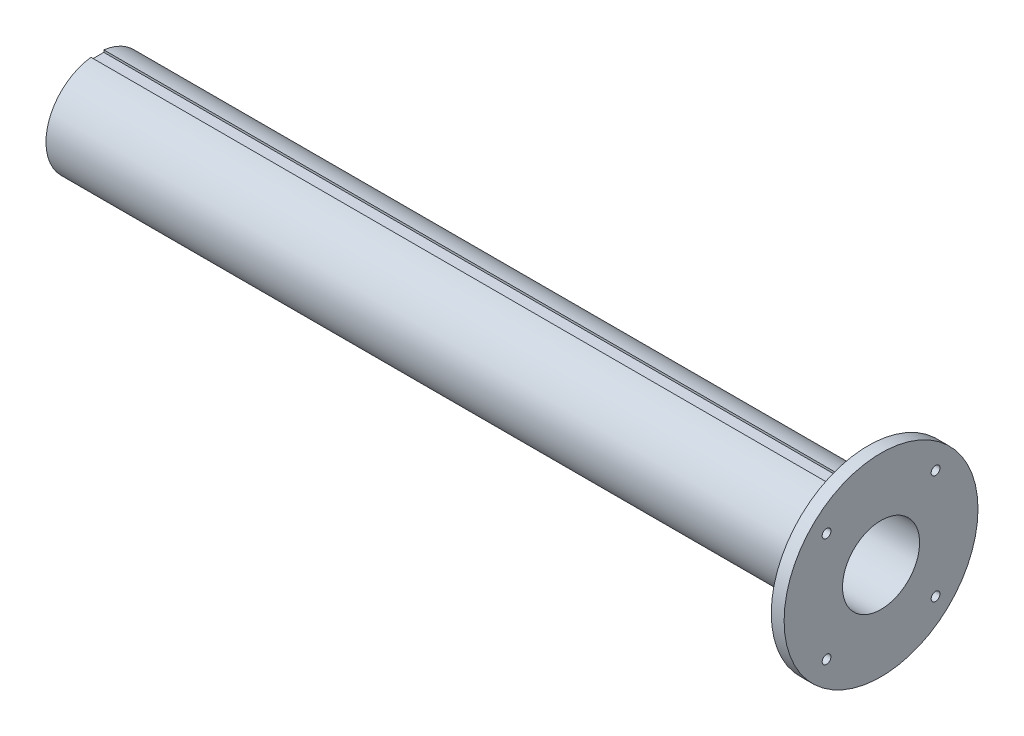
SolidWorks part; units mm, degrees
material "AISI 304"
ref_plane "前视基准面" through (0, 0, 0) normal (0, 0, 1) x (1, 0, 0)
ref_plane "上视基准面" through (0, 0, 0) normal (0, 1, 0) x (1, 0, 0)
ref_plane "右视基准面" through (0, 0, 0) normal (1, 0, 0) x (0, 0, -1)
sketch "Sketch1" plane through (0, 0, 0) normal (0, 0, 1) x (1, 0, 0)
  line L0 (-108.2712, 10) -> (-108.2712, 0)
  line L3 (-108.2712, 0) -> (491.7288, 0)
  line L4 (491.7288, 0) -> (491.7288, -35.4626)
  line L5 (491.7288, -35.4626) -> (501.7288, -35.4626)
  line L6 (501.7288, -35.4626) -> (501.7288, 10)
  line L7 (501.7288, 10) -> (-108.2712, 10)
  line L8 (-148.4581, 40) -> (137.0044, 40) construction
  dimension "D1" = 40
  dimension "D2" = 10
  dimension "D3" = 610
  dimension "D5" = 10
revolve "Revolve1" add sketch "Sketch1" angle 360 about L8
sketch "Sketch2" plane through (-108.2712, 0, 0) normal (-1, 0, 0) x (0, 0, 1)
  line L0 (0, 80) -> (0, 0) construction
  line L2 (-5, 82) -> (5, 82)
  line L3 (-5, 82) -> (-5, 78)
  line L4 (-5, 78) -> (5, 78)
  line L5 (5, 82) -> (5, 78)
  line L6 (-5, 82) -> (5, 78) construction
  line L7 (-5, 78) -> (5, 82) construction
  circle A0 centre (0, 40) radius 40 construction
  circle A1 centre (0, 40) radius 40 construction
  dimension "D1" = 4
  dimension "D2" = 10
extrude "Extrude1" cut sketch "Sketch2" against normal blind 600
sketch "Sketch3" plane through (501.7288, 0, 0) normal (1, 0, 0) x (0, 0, -1)
  line L1 (42.4264, -2.4264) -> (-42.4264, -2.4264) construction
  line L2 (42.4264, -2.4264) -> (42.4264, 82.4264) construction
  line L3 (42.4264, 82.4264) -> (-42.4264, 82.4264) construction
  line L4 (-42.4264, -2.4264) -> (-42.4264, 82.4264) construction
  line L5 (42.4264, -2.4264) -> (-42.4264, 82.4264) construction
  line L6 (42.4264, 82.4264) -> (-42.4264, -2.4264) construction
  circle A0 centre (0, 40) radius 60 construction
  dimension "D1" = 120
hole_wizard "M8 Tapped Hole1" positions "3DSketch1" profile "Sketch4" tap size "M8" standard "GB"
sketch3d "3DSketch1"
  point P0 (501.7288, 82.4264, 42.4264)
  point P3 (501.7288, 82.4264, -42.4264)
  point P6 (501.7288, -2.4264, -42.4264)
  point P9 (501.7288, -2.4264, 42.4264)
sketch "Sketch4" plane through (501.7288, 82.4264, 42.4264) normal (0, 1, 0) x (0, 0, -1)
  line L0 (0, 0) -> (0, 21.7929)
  line L1 (0, 21.7929) -> (3.4, 19.75)
  line L2 (3.4, 19.75) -> (3.4, 0)
  line L5 (3.4, 0) -> (0, 0)
  line L10 (0, 21.7929) -> (-3.4, 19.75) construction
  line L11 (0, -6.35) -> (0, 107.95) construction
  dimension "螺纹孔钻头直径" = 6.8
  dimension "螺纹孔钻头深度" = 19.75
  dimension "导头角度" = 118
cosmetic thread "Cosmetic Thread1" parameters "D1"=10, "D2"=8
cosmetic thread "Cosmetic Thread2" parameters "D1"=10, "D2"=8
cosmetic thread "Cosmetic Thread3" parameters "D1"=10, "D2"=8
cosmetic thread "Cosmetic Thread4" parameters "D1"=10, "D2"=8
